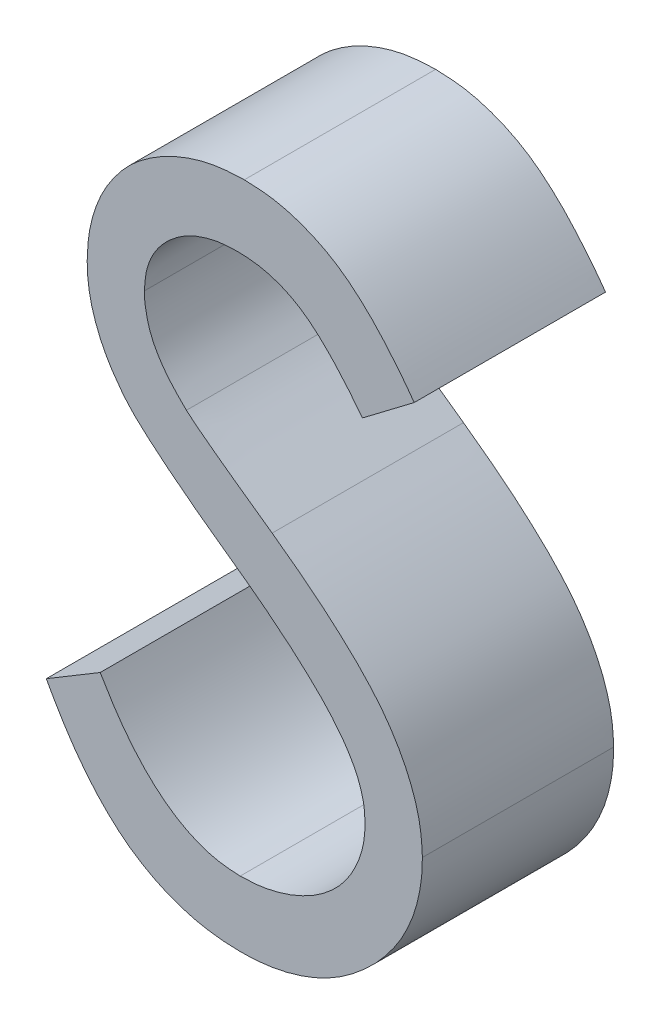
SolidWorks part; units mm, degrees
ref_plane "Plan de face" through (0, 0, 0) normal (0, 0, 1) x (1, 0, 0)
ref_plane "Plan de dessus" through (0, 0, 0) normal (0, 1, 0) x (1, 0, 0)
ref_plane "Plan de droite" through (0, 0, 0) normal (1, 0, 0) x (0, 0, -1)
sketch "Esquisse1" plane through (0, 0, 0) normal (0, 0, 1) x (1, 0, 0)
  text T0 "S" font "Century Gothic" height 5
extrude "Boss.-Extru.1" add sketch "Esquisse1" along normal blind 1.5
